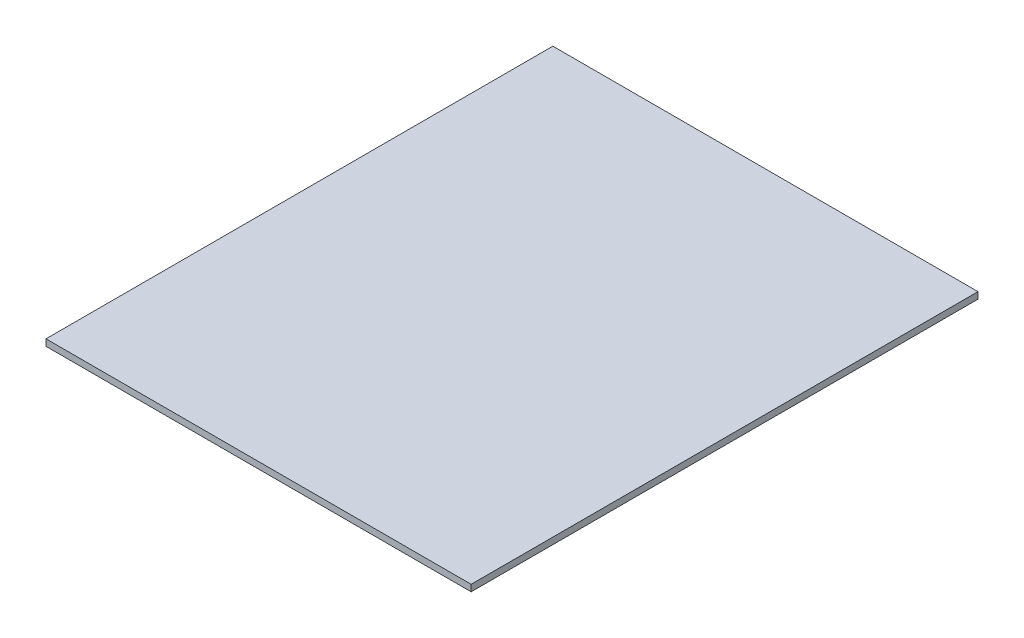
SolidWorks part; units mm, degrees
ref_plane "Front Plane" through (0, 0, 0) normal (0, 0, 1) x (1, 0, 0)
ref_plane "Top Plane" through (0, 0, 0) normal (0, 1, 0) x (1, 0, 0)
ref_plane "Right Plane" through (0, 0, 0) normal (1, 0, 0) x (0, 0, -1)
sketch "Sketch1" plane through (0, 0, 0) normal (0, 1, 0) x (1, 0, 0)
  line L1 (-325, -387.475) -> (325, -387.475)
  line L2 (-325, -387.475) -> (-325, 387.475)
  line L3 (-325, 387.475) -> (325, 387.475)
  line L4 (325, -387.475) -> (325, 387.475)
  line L5 (-325, -387.475) -> (325, 387.475) construction
  line L6 (-325, 387.475) -> (325, -387.475) construction
  point P0 (0, 0)
  dimension "D1" = 650
  dimension "D2" = 774.95
extrude "Boss-Extrude1" add sketch "Sketch1" along normal blind 10
sketch "Sketch2" plane through (0, 0, 0) normal (0, -1, 0) x (1, 0, 0)
  line L0 (-325, 387.475) -> (325, 387.475) construction
  line L1 (-325, -387.475) -> (-325, 387.475) construction
  circle A0 centre (-203.532, 369.975) radius 3
  circle A1 centre (196.468, 369.975) radius 3
  dimension "D1" = 6
  dimension "D2" = 6
  dimension "D3" = 17.5
  dimension "D4" = 17.5
  dimension "D5" = 400
  dimension "D6" = 121.468
extrude "Boss-Extrude2" add sketch "Sketch2" along normal blind 10
mirror "Mirror1" about plane through (0, 0, 0) normal (0, 0, 1) of "Boss-Extrude2"
